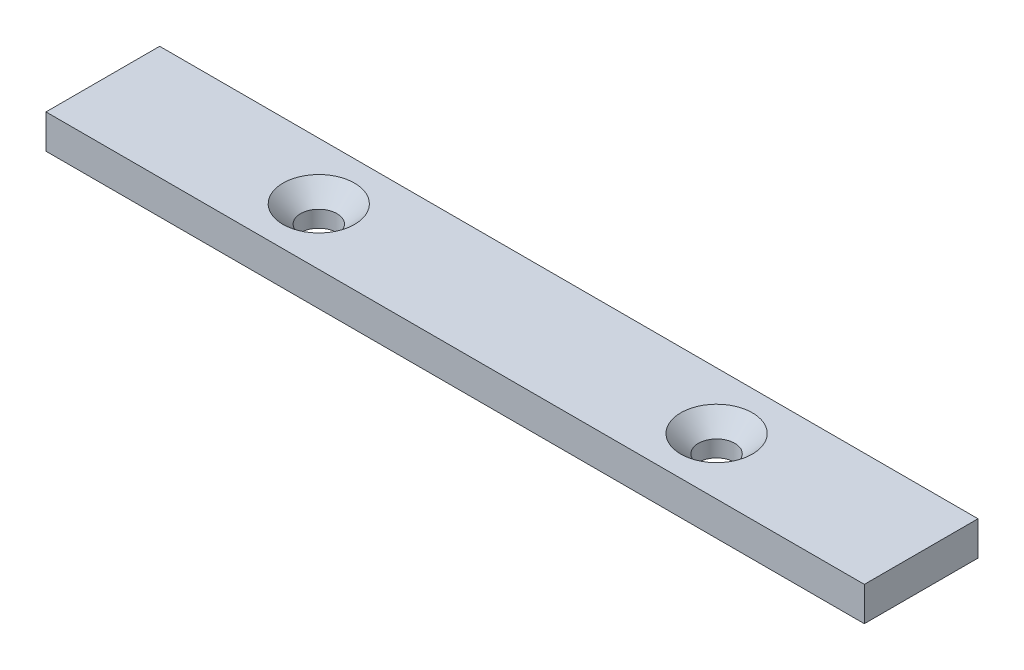
SolidWorks part; units mm, degrees
ref_plane "Front Plane" through (0, 0, 0) normal (0, 0, 1) x (1, 0, 0)
ref_plane "Top Plane" through (0, 0, 0) normal (0, 1, 0) x (1, 0, 0)
ref_plane "Right Plane" through (0, 0, 0) normal (1, 0, 0) x (0, 0, -1)
sketch "Sketch1" plane through (0, 0, 0) normal (0, 1, 0) x (1, 0, 0)
  line L0 (0, 0) -> (0, -20)
  line L1 (0, 0) -> (144, 0)
  line L2 (0, -20) -> (144, -20)
  line L3 (144, -20) -> (144, 0)
  line L4 (0, -10) -> (38, -10) construction
  line L5 (38, -10) -> (108, -10) construction
  dimension "D1" = 20
  dimension "D2" = 144
  dimension "D3" = 70
  dimension "D4" = 38
extrude "Boss-Extrude1" add sketch "Sketch1" along normal blind 6
hole_wizard "CSK for M6 Flat Head Machine Screw1" positions "Sketch2" profile "Sketch3" countersink size "M6" standard "ANSI Metric" end condition through all
sketch "Sketch2" plane through (0, 6, 0) normal (0, 1, 0) x (1, 0, 0)
  point P0 (38, -10)
  point P3 (108, -10)
sketch "Sketch3" plane through (38, 6, 10) normal (1, 0, 0) x (0, 0, 1)
  line L0 (0, 0) -> (0, 6)
  line L1 (0, 6) -> (3.2, 6)
  line L2 (3.2, 6) -> (3.2, 3.1)
  line L3 (3.2, 3.1) -> (6.3, 0)
  line L5 (6.3, 0) -> (0, 0)
  line L6 (-3.2, 3.1) -> (-6.3, 0) construction
  line L11 (0, -6.35) -> (0, 107.95) construction
  dimension "Thru Hole Dia." = 6.4
  dimension "Thru Hole Depth" = 6
  dimension "Near C'Sink Dia." = 12.6
  dimension "Near C'Sink Angle" = 90
